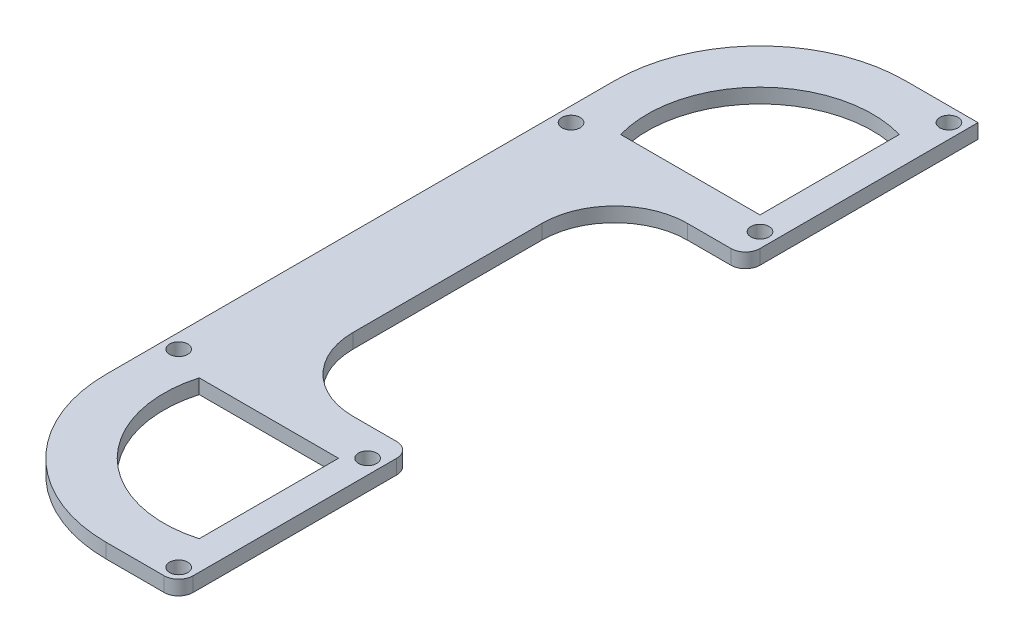
SolidWorks part; units mm, degrees
material "Thornel Mat VMA"
ref_plane "前视基准面" through (0, 0, 0) normal (0, 0, 1) x (1, 0, 0)
ref_plane "上视基准面" through (0, 0, 0) normal (0, 1, 0) x (1, 0, 0)
ref_plane "右视基准面" through (0, 0, 0) normal (1, 0, 0) x (0, 0, -1)
sketch "草图1" plane through (0, 0, 0) normal (0, 1, 0) x (1, 0, 0)
  line L1 (-15, 55) -> (15, 55)
  line L2 (-15, 55) -> (-15, -55)
  line L3 (-15, -55) -> (15, -55)
  line L4 (15, 55) -> (15, -55)
  line L5 (0, -55) -> (0, 55) construction
  line L6 (-15, 0) -> (15, 0) construction
  point P0 (0, 0)
  dimension "D1" = 30
  dimension "D2" = 110
extrude "凸台-拉伸1" add sketch "草图1" along normal blind 2
sketch "草图2" plane through (0, 2, 0) normal (0, 1, 0) x (1, 0, 0)
  line L0 (0, 55) -> (0, -55) construction
  line L1 (15, 55) -> (-15, 55) construction
  line L2 (-15, -55) -> (15, -55) construction
  line L3 (-15, 0) -> (15, 0) construction
  line L4 (-15, 55) -> (-15, -55) construction
  line L5 (15, -55) -> (15, 55) construction
  line L6 (13, 27) -> (13, 54.5501) construction
  line L7 (13, -27) -> (13, -54.5501) construction
  circle A0 centre (13, 27) radius 1.25
  circle A1 centre (-13, 27) radius 1.25
  circle A2 centre (13, 53) radius 1.25
  circle A3 centre (13, -53) radius 1.25
  circle A4 centre (-13, -27) radius 1.25
  circle A5 centre (13, -27) radius 1.25
  dimension "D1" = 26
  dimension "D2" = 2.5
  dimension "D3" = 2.5
  dimension "D4" = 26
  dimension "D5" = 54
extrude "切除-拉伸1" cut sketch "草图2" against normal blind 2
fillet "圆角1" radius 20 2 edges at (-15, 1, 55) (-15, 1, -55)
fillet "圆角2" radius 2 1 edges at (15, 1, 55)
sketch "草图3" plane through (0, 2, 0) normal (0, 1, 0) x (1, 0, 0)
  line L0 (-15, 0) -> (15, 0) construction
  line L1 (-15, 35) -> (-15, -35) construction
  line L2 (15, -53) -> (15, 55) construction
  line L3 (15, -23) -> (15, 23)
  line L4 (15, 23) -> (-3, 23)
  line L5 (-3, 23) -> (-3, -23)
  line L6 (-3, -23) -> (15, -23)
  point P10 (15, 0)
  dimension "D1" = 18
  dimension "D2" = 46
extrude "切除-拉伸2" cut sketch "草图3" against normal blind 2
fillet "圆角4" radius 10 2 edges at (-3, 1, 23) (-3, 1, -23)
fillet "圆角5" radius 2 2 edges at (15, 1, 23) (15, 1, -23)
sketch "草图4" plane through (0, 2, 0) normal (0, 1, 0) x (1, 0, 0)
  line L0 (13, 53) -> (13, 27) construction
  line L1 (13, 27) -> (-13, 27) construction
  line L2 (-13, 27) -> (13, 53) construction
  line L3 (-29.9255, 0) -> (44.2094, 0) construction
  line L4 (11, 48.1716) -> (11, 29)
  line L5 (11, 29) -> (-8.1716, 29)
  line L6 (-8.1716, 29) -> (11, 48.1716) construction
  line L7 (-8.1716, -29) -> (11, -48.1716) construction
  line L8 (-13, -27) -> (13, -53) construction
  line L9 (13, -27) -> (-13, -27) construction
  line L10 (13, -53) -> (13, -27) construction
  line L13 (11, -29) -> (-8.1716, -29)
  line L14 (11, -48.1716) -> (11, -29)
  arc A2 (11, 48.1716) -> (-8.1716, 29) centre (6.7352, 33.2648) ccw
  arc A3 (11, -48.1716) -> (-8.1716, -29) centre (6.7352, -33.2648) cw
  dimension "D1" = 2
  dimension "D2" = 2
  dimension "D3" = 2
extrude "切除-拉伸3" cut sketch "草图4" against normal blind 10
